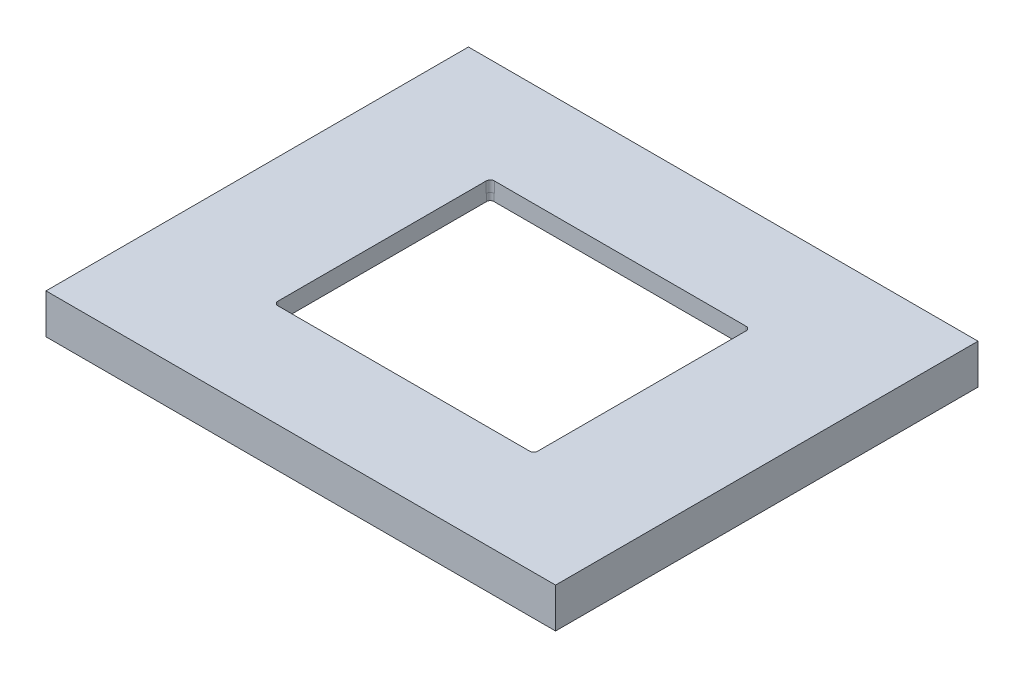
SolidWorks part; units mm, degrees
ref_plane "Front Plane" through (0, 0, 0) normal (0, 0, 1) x (1, 0, 0)
ref_plane "Top Plane" through (0, 0, 0) normal (0, 1, 0) x (1, 0, 0)
ref_plane "Right Plane" through (0, 0, 0) normal (1, 0, 0) x (0, 0, -1)
sketch "Sketch1" plane through (0, 0, 0) normal (0, 1, 0) x (1, 0, 0)
  line L0 (35.205, -29.185) -> (35.205, 29.185)
  line L1 (33.205, -27.185) -> (-33.205, -27.185)
  line L2 (33.205, -27.185) -> (33.205, 27.185)
  line L3 (33.205, 27.185) -> (-33.205, 27.185)
  line L4 (-33.205, -27.185) -> (-33.205, 27.185)
  line L5 (33.205, -27.185) -> (-33.205, 27.185) construction
  line L6 (33.205, 27.185) -> (-33.205, -27.185) construction
  line L7 (35.205, 29.185) -> (-35.205, 29.185)
  line L8 (-35.205, -29.185) -> (-35.205, 29.185)
  line L9 (35.205, -29.185) -> (-35.205, -29.185)
  point P0 (0, 0)
  dimension "D1" = 54.37
  dimension "D2" = 66.41
  dimension "D3" = 2
extrude "Boss-Extrude1" add sketch "Sketch1" along normal blind 4
sketch "Sketch2" plane through (0, 4, 0) normal (0, 1, 0) x (1, 0, 0)
  line L1 (-17.95, -14.95) -> (17.95, -14.95)
  line L2 (-17.95, -14.95) -> (-17.95, 14.95)
  line L3 (-17.95, 14.95) -> (17.95, 14.95)
  line L4 (17.95, -14.95) -> (17.95, 14.95)
  line L5 (-17.95, -14.95) -> (17.95, 14.95) construction
  line L6 (-17.95, 14.95) -> (17.95, -14.95) construction
  line L7 (35.205, -29.185) -> (-35.205, -29.185)
  line L8 (35.205, -29.185) -> (35.205, 29.185)
  line L9 (35.205, 29.185) -> (-35.205, 29.185)
  line L10 (-35.205, -29.185) -> (-35.205, 29.185)
  line L11 (35.205, -29.185) -> (-35.205, 29.185) construction
  line L12 (35.205, 29.185) -> (-35.205, -29.185) construction
  point P0 (0, 0)
  point P6 (0, 0)
  dimension "D1" = 35.9
  dimension "D2" = 29.9
extrude "Boss-Extrude2" add sketch "Sketch2" along normal blind 1.5
fillet "Fillet1" radius 0.56 4 edges at (17.95, 4.75, 14.95) (-17.95, 4.75, 14.95) (17.95, 4.75, -14.95) (-17.95, 4.75, -14.95)
sketch "Sketch3" plane through (0, 4, 0) normal (0, -1, 0) x (1, 0, 0)
  line L0 (18.95, -14.45) -> (18.95, 14.45)
  line L1 (17.45, -14.95) -> (-17.45, -14.95)
  line L2 (17.95, -14.45) -> (17.95, 14.45)
  line L3 (17.45, 14.95) -> (-17.45, 14.95)
  line L4 (-17.95, -14.45) -> (-17.95, 14.45)
  line L5 (17.95, -14.95) -> (-17.95, 14.95) construction
  line L6 (17.95, 14.95) -> (-17.95, -14.95) construction
  line L7 (17.45, 15.95) -> (-17.45, 15.95)
  line L8 (-18.95, -14.45) -> (-18.95, 14.45)
  line L9 (17.45, -15.95) -> (-17.45, -15.95)
  arc A0 (-17.95, 14.45) -> (-17.45, 14.95) centre (-17.45, 14.45) cw
  arc A1 (-17.45, -14.95) -> (-17.95, -14.45) centre (-17.45, -14.45) cw
  arc A2 (17.45, 14.95) -> (17.95, 14.45) centre (17.45, 14.45) cw
  arc A3 (17.45, -14.95) -> (17.95, -14.45) centre (17.45, -14.45) ccw
  arc A4 (17.45, 15.95) -> (18.95, 14.45) centre (17.45, 14.45) cw
  arc A5 (-18.95, 14.45) -> (-17.45, 15.95) centre (-17.45, 14.45) cw
  arc A6 (-17.45, -15.95) -> (-18.95, -14.45) centre (-17.45, -14.45) cw
  arc A7 (17.45, -15.95) -> (18.95, -14.45) centre (17.45, -14.45) ccw
  point P0 (0, 0)
  dimension "D1" = 0.5
  dimension "D2" = 0.5
  dimension "D3" = 0.5
  dimension "D4" = 0.5
  dimension "D5" = 1
extrude "Boss-Extrude3" add sketch "Sketch3" along normal blind 1
